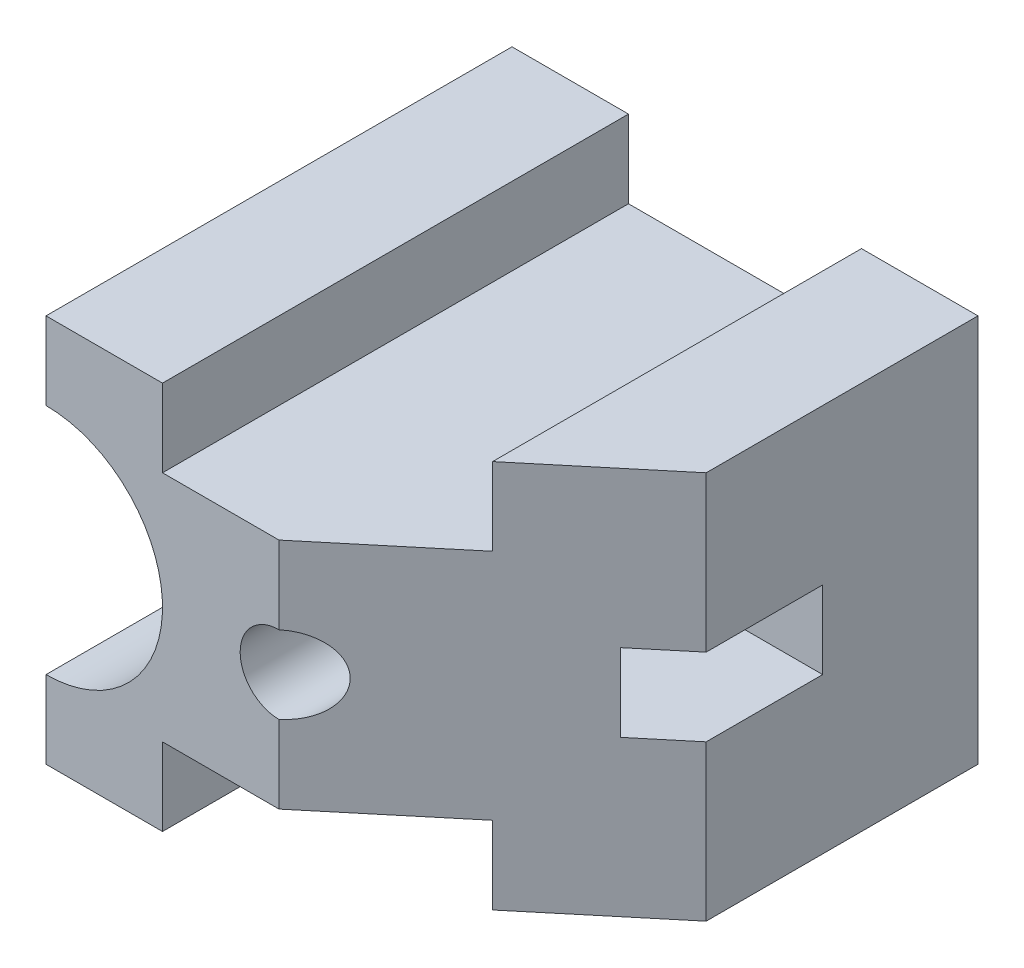
SolidWorks part; units mm, degrees
ref_plane "Front Plane" through (0, 0, 0) normal (0, 0, 1) x (1, 0, 0)
ref_plane "Top Plane" through (0, 0, 0) normal (0, 1, 0) x (1, 0, 0)
ref_plane "Right Plane" through (0, 0, 0) normal (1, 0, 0) x (0, 0, -1)
sketch "Sketch1" plane through (0, 0, 0) normal (0, 0, 1) x (1, 0, 0)
  line L0 (-23.2031, -22.8906) -> (-23.2031, -32.8906)
  line L1 (-38.2031, 17.1094) -> (-23.2031, 17.1094)
  line L2 (-38.2031, 17.1094) -> (-38.2031, 7.1094)
  line L3 (-38.2031, -32.8906) -> (-23.2031, -32.8906)
  line L4 (-23.2031, 17.1094) -> (-23.2031, 7.1094)
  line L5 (-23.2031, 7.1094) -> (6.7969, 7.1094)
  line L7 (-23.2031, -22.8906) -> (6.7969, -22.8906)
  line L9 (6.7969, 17.1094) -> (21.7969, 17.1094)
  line L10 (6.7969, 17.1094) -> (6.7969, 7.1094)
  line L11 (6.7969, -32.8906) -> (21.7969, -32.8906)
  line L12 (21.7969, 17.1094) -> (21.7969, -32.8906)
  line L13 (6.7969, -22.8906) -> (6.7969, -32.8906)
  line L14 (-38.2031, -22.8906) -> (-38.2031, -32.8906)
  line L15 (-8.2031, 7.1094) -> (-8.2031, -22.8906) construction
  arc A0 (-38.2031, -22.8906) -> (-38.2031, 7.1094) centre (-38.2031, -7.8906) ccw
  circle A1 centre (-8.2031, -7.8906) radius 5
  dimension "D7" = 30
  dimension "D8" = 10
  dimension "D1" = 15
  dimension "D2" = 50
  dimension "D3" = 30
  dimension "D4" = 30
  dimension "D5" = 15
  dimension "D6" = 50
extrude "Boss-Extrude1" add sketch "Sketch1" along normal blind 60
sketch "Sketch3" plane through (0, 17.1094, 0) normal (0, 1, 0) x (1, 0, 0)
  line L0 (21.7969, -60) -> (21.7969, -35) construction
  line L1 (21.7969, -60) -> (21.7969, 0) construction
  line L2 (-8.2031, -60) -> (21.7969, -35)
  line L3 (6.7969, -60) -> (-23.2031, -60) construction
  line L4 (21.7969, -35) -> (21.7969, -60)
  line L5 (21.7969, -60) -> (-8.2031, -60)
  dimension "D1" = 25
extrude "Cut-Extrude3" cut sketch "Sketch3" against normal blind 60
sketch "Sketch7" plane through (21.7969, 0, 0) normal (1, 0, 0) x (0, 0, -1)
  line L0 (-60, -7.8906) -> (-40, -7.8906) construction
  line L1 (-60, -2.8906) -> (-60, -12.8906) construction
  line L3 (-40, -2.8906) -> (-20, -2.8906)
  line L4 (-40, -2.8906) -> (-40, -12.8906)
  line L5 (-40, -12.8906) -> (-20, -12.8906)
  line L6 (-20, -2.8906) -> (-20, -12.8906)
  dimension "D1" = 20
  dimension "D2" = 20
  dimension "D3" = 10
extrude "Cut-Extrude4" cut sketch "Sketch7" against normal blind 60
